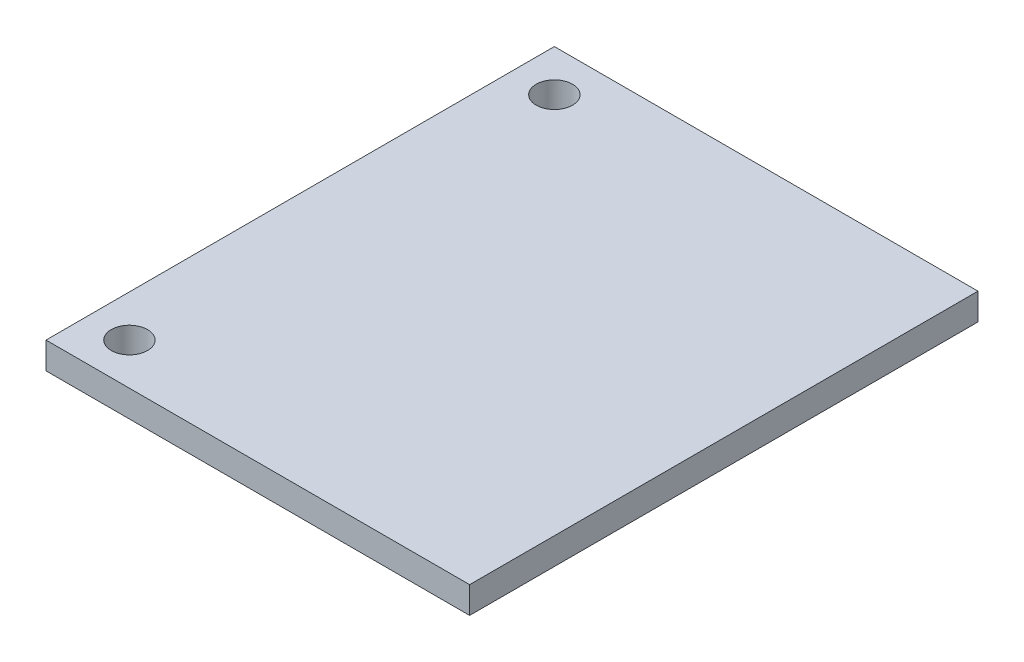
SolidWorks part; units mm, degrees
ref_plane "Front" through (0, 0, 0) normal (0, 0, 1) x (1, 0, 0)
ref_plane "Top" through (0, 0, 0) normal (0, 1, 0) x (1, 0, 0)
ref_plane "Right" through (0, 0, 0) normal (1, 0, 0) x (0, 0, -1)
sketch "Sketch1" plane through (0, 0, 0) normal (0, 1, 0) x (1, 0, 0)
  line L1 (-12.7, 15.24) -> (12.7, 15.24)
  line L2 (-12.7, 15.24) -> (-12.7, -15.24)
  line L3 (-12.7, -15.24) -> (12.7, -15.24)
  line L4 (12.7, 15.24) -> (12.7, -15.24)
  line L5 (-12.7, 15.24) -> (12.7, -15.24) construction
  line L6 (-12.7, -15.24) -> (12.7, 15.24) construction
  point P0 (0, 0)
  dimension "D1" = 25.4
  dimension "D2" = 30.48
extrude "Boss-Extrude1" add sketch "Sketch1" along normal blind 1.6
sketch "Sketch2" plane through (0, 1.6, 0) normal (0, 1, 0) x (1, 0, 0)
  line L0 (-12.7, 15.24) -> (-12.7, -15.24) construction
  line L2 (12.7, 15.24) -> (-12.7, 15.24) construction
  circle A0 centre (-10.2, 12.74) radius 1.09
  dimension "D1" = 2.18
  dimension "D2" = 2.5
  dimension "D3" = 2.5
extrude "Cut-Extrude1" cut sketch "Sketch2" against normal blind 1.6
mirror "Mirror1" about plane through (0, 0, 0) normal (0, 0, 1) of "Cut-Extrude1"
